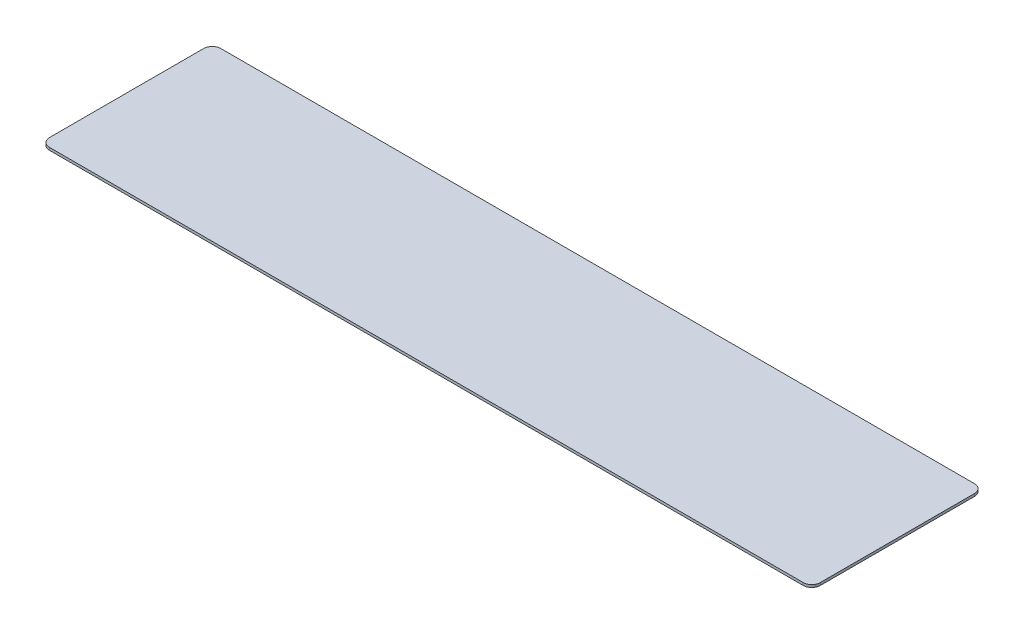
SolidWorks part; units mm, degrees
ref_plane "Plan de face" through (0, 0, 0) normal (0, 0, 1) x (1, 0, 0)
ref_plane "Plan de dessus" through (0, 0, 0) normal (0, 1, 0) x (1, 0, 0)
ref_plane "Plan de droite" through (0, 0, 0) normal (1, 0, 0) x (0, 0, -1)
sketch "Sketch1" plane through (0, 0, 0) normal (0, 1, 0) x (1, 0, 0)
  line L1 (0, 0) -> (900, 0)
  line L2 (0, 0) -> (0, 200)
  line L3 (0, 200) -> (900, 200)
  line L4 (900, 0) -> (900, 200)
  dimension "D1" = 900
  dimension "D2" = 200
extrude "Boss-Extrude1" add sketch "Sketch1" along normal blind 3
fillet "Fillet2" radius 10 4 edges at (900, 1.5, 0) (900, 1.5, -200) (0, 1.5, -200) (0, 1.5, 0)
